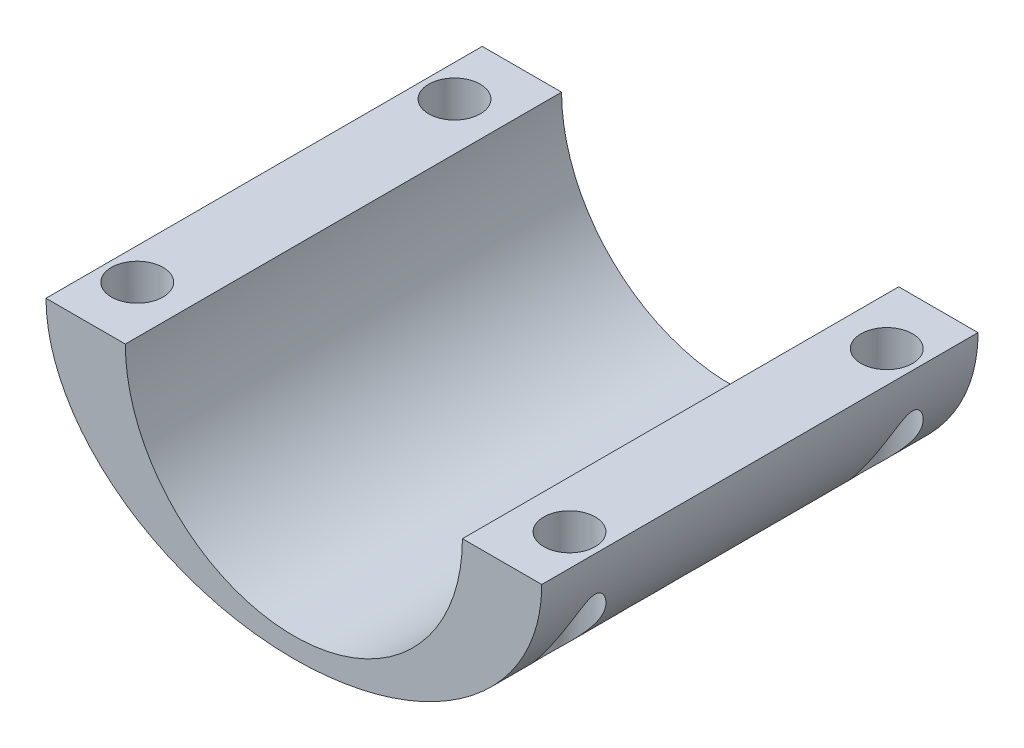
SolidWorks part; units mm, degrees
ref_plane "Plan de face" through (0, 0, 0) normal (0, 0, 1) x (1, 0, 0)
ref_plane "Plan de dessus" through (0, 0, 0) normal (0, 1, 0) x (1, 0, 0)
ref_plane "Plan de droite" through (0, 0, 0) normal (1, 0, 0) x (0, 0, -1)
sketch "Esquisse1" plane through (0, 0, 0) normal (0, 0, 1) x (1, 0, 0)
  line L0 (-17.9494, -9.5) -> (-5.4494, -9.5)
  line L1 (-30.4494, 0) -> (-5.4494, 0)
  line L2 (-17.9494, -9.5) -> (-30.4494, -9.5)
  line L3 (-30.4494, 0) -> (-30.4494, -9.5)
  line L4 (-5.4494, 0) -> (-5.4494, -9.5)
  circle A0 centre (-17.9494, 0) radius 8.5
  ellipse E0 centre (-17.9494, 0) end of major axis (-5.4494, 0) minor radius 9.5
  dimension "D1" = 17
  dimension "D3" = 25
  dimension "D4" = 12.5
extrude "Boss.-Extru.1" add sketch "Esquisse1" along normal blind 22 contours A0 L1 L3 L2 L0 L4
sketch "Esquisse2" plane through (0, 0, 0) normal (0, 1, 0) x (1, 0, 0)
  line L4 (-30.4494, -22) -> (-26.4494, -22) construction
  line L5 (-30.4494, 0) -> (-26.4494, 0) construction
  line L6 (-9.4494, 0) -> (-5.4494, 0) construction
  line L8 (-9.4494, -22) -> (-5.4494, -22) construction
  line L9 (-30.4494, -22) -> (-30.4494, 0) construction
  circle A0 centre (-28.8494, -3) radius 1.3
  circle A1 centre (-28.8494, -19) radius 1.3
  circle A2 centre (-7.0494, -3) radius 1.3
  circle A3 centre (-7.0494, -19) radius 1.3
  point P4 (0, 0)
  dimension "D1" = 2.6
  dimension "D3" = 3
  dimension "D2" = 2.6
  dimension "D6" = 2.6
  dimension "D7" = 2.6
  dimension "D4" = 3
  dimension "D5" = 3
  dimension "D8" = 3
  dimension "D9" = 1.6
extrude "Enlèv. mat.-Extru.1" cut sketch "Esquisse2" against normal through all
